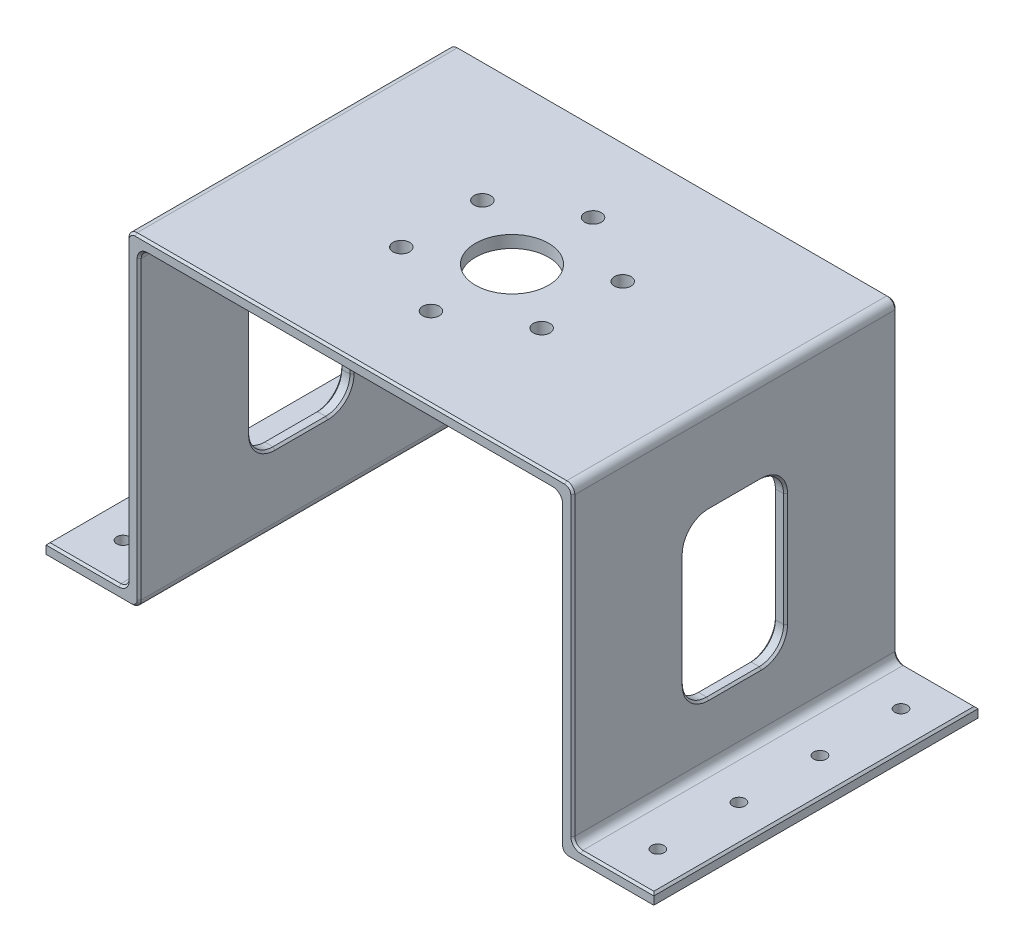
SolidWorks part; units mm, degrees
material "6061 合金"
ref_plane "前视基准面" through (0, 0, 0) normal (0, 0, 1) x (1, 0, 0)
ref_plane "上视基准面" through (0, 0, 0) normal (0, 1, 0) x (1, 0, 0)
ref_plane "右视基准面" through (0, 0, 0) normal (1, 0, 0) x (0, 0, -1)
sketch "草图1" plane through (0, 0, 0) normal (0, 0, 1) x (1, 0, 0)
  line L0 (-52, 0) -> (52, 0)
  line L1 (0, 0) -> (0, 3) construction
  line L2 (-55, 3) -> (55, 3)
  line L3 (-52, 0) -> (-52, -77)
  line L4 (-55, 3) -> (-55, -74)
  line L5 (-55, -74) -> (-75, -74)
  line L6 (-52, -77) -> (-75, -77)
  line L7 (-75, -74) -> (-75, -77)
  line L8 (75, -74) -> (75, -77)
  line L9 (52, -77) -> (75, -77)
  line L10 (55, -74) -> (75, -74)
  line L11 (55, 3) -> (55, -74)
  line L12 (52, 0) -> (52, -77)
extrude "凸台-拉伸1" add sketch "草图1" along normal blind 80
fillet "圆角1" radius 2 8 edges at (55, 3, 40) (-55, 3, 40) (-52, 0, 40) (52, 0, 40) (55, -74, 40) (52, -77, 40) (-52, -77, 40) (-55, -74, 40)
sketch "草图2" plane through (0, 3, 0) normal (0, 1, 0) x (1, 0, 0)
  circle A0 centre (0, -40) radius 20 construction
  circle A1 centre (-17.3205, -30) radius 2.05
  circle A2 centre (0, -20) radius 2.05
  circle A3 centre (17.3205, -30) radius 2.05
  circle A4 centre (17.3205, -50) radius 2.05
  circle A5 centre (0, -40) radius 9
  circle A6 centre (0, -60) radius 2.05
  circle A7 centre (-17.3205, -50) radius 2.05
  point P13 (0, -40)
  point P19 (0, -40)
  dimension "D1" = 40
  dimension "D2" = 4.1
  dimension "D4" = 18
  dimension "D3" = 6
extrude "yaw电机固定" cut sketch "草图2" against normal up to next
sketch "草图3" plane through (0, -74, 0) normal (0, 1, 0) x (1, 0, 0)
  line L0 (-57, 0) -> (-75, 0) construction
  line L1 (-66, -10) -> (-66, -30) construction
  line L2 (0, 0) -> (0, -35.7216) construction
  circle A0 centre (-66, -10) radius 1.55
  circle A1 centre (-66, -30) radius 1.55
  circle A2 centre (-66, -50) radius 1.55
  circle A3 centre (-66, -70) radius 1.55
  circle A4 centre (66, -70) radius 1.55
  circle A5 centre (66, -50) radius 1.55
  circle A6 centre (66, -30) radius 1.55
  circle A7 centre (66, -10) radius 1.55
  point P2 (-66, 0)
  dimension "D1" = 3.1
  dimension "D2" = 10
  dimension "D4" = 20
  dimension "D3" = 4
extrude "切除-拉伸2" cut sketch "草图3" against normal up to next
sketch "草图4" plane through (-55, 0, 0) normal (-1, 0, 0) x (0, 0, 1)
  line L0 (0, 1) -> (0, -72) construction
  line L1 (27.5, -19) -> (52.5, -19)
  line L2 (27.5, -19) -> (27.5, -59)
  line L3 (27.5, -59) -> (52.5, -59)
  line L4 (52.5, -19) -> (52.5, -59)
  line L5 (27.5, -19) -> (52.5, -59) construction
  line L6 (27.5, -59) -> (52.5, -19) construction
  line L7 (80, -74) -> (0, -74) construction
  point P0 (40, -39)
  dimension "D1" = 25
  dimension "D2" = 40
  dimension "D3" = 40
  dimension "D4" = 35
extrude "切除-拉伸3" cut sketch "草图4" against normal through all
fillet "圆角2" radius 6 8 edges at (53.5, -19, 27.5) (53.5, -19, 52.5) (53.5, -59, 52.5) (53.5, -59, 27.5) (-53.5, -59, 27.5) (-53.5, -59, 52.5) (-53.5, -19, 52.5) (-53.5, -19, 27.5)
chamfer "倒角1" distance 0.5 angle 45 72 edges at (-64.5, -77, 0) (64.5, -77, 0) (-52.5858, -76.4142, 0) (52.5858, -76.4142, 0) (-52, -38.5, 0) (52, -38.5, 0) (-51.4142, -0.5858, 0) (51.4142, -0.5858, 0) (0, 0, 0) (66, -74, 0) (-66, -74, 0) (55.5858, -73.4142, 0) (-55.5858, -73.4142, 0) (55, -35.5, 0) (-55, -35.5, 0) (54.4142, 2.4142, 0) (-54.4142, 2.4142, 0) (0, 3, 0) (66, -74, 80) (-66, -74, 80) (55.5858, -73.4142, 80) (-55.5858, -73.4142, 80) (55, -35.5, 80) (-55, -35.5, 80) (54.4142, 2.4142, 80) (-54.4142, 2.4142, 80) (0, 3, 80) (-64.5, -77, 80) (64.5, -77, 80) (-52.5858, -76.4142, 80) (52.5858, -76.4142, 80) (-52, -38.5, 80) (52, -38.5, 80) (-51.4142, -0.5858, 80) (51.4142, -0.5858, 80) (0, 0, 80) (75, -77, 40) (75, -74, 40) (55, -19, 40) (55, -20.7574, 29.2574) (55, -20.7574, 50.7426) (55, -39, 27.5) (55, -39, 52.5) (55, -57.2426, 29.2574) (55, -57.2426, 50.7426) (55, -59, 40) (52, -19, 40) (52, -20.7574, 50.7426) (52, -20.7574, 29.2574) (52, -39, 52.5) (52, -39, 27.5) (52, -57.2426, 50.7426) (52, -57.2426, 29.2574) (52, -59, 40) (-52, -39, 27.5) (-52, -57.2426, 29.2574) (-52, -20.7574, 29.2574) (-52, -59, 40) (-52, -19, 40) (-52, -57.2426, 50.7426) (-52, -20.7574, 50.7426) (-52, -39, 52.5) (-55, -19, 40) (-55, -20.7574, 29.2574) (-55, -20.7574, 50.7426) (-55, -39, 27.5) (-55, -39, 52.5) (-55, -57.2426, 29.2574) (-55, -57.2426, 50.7426) (-55, -59, 40) (-75, -77, 40) (-75, -74, 40)
